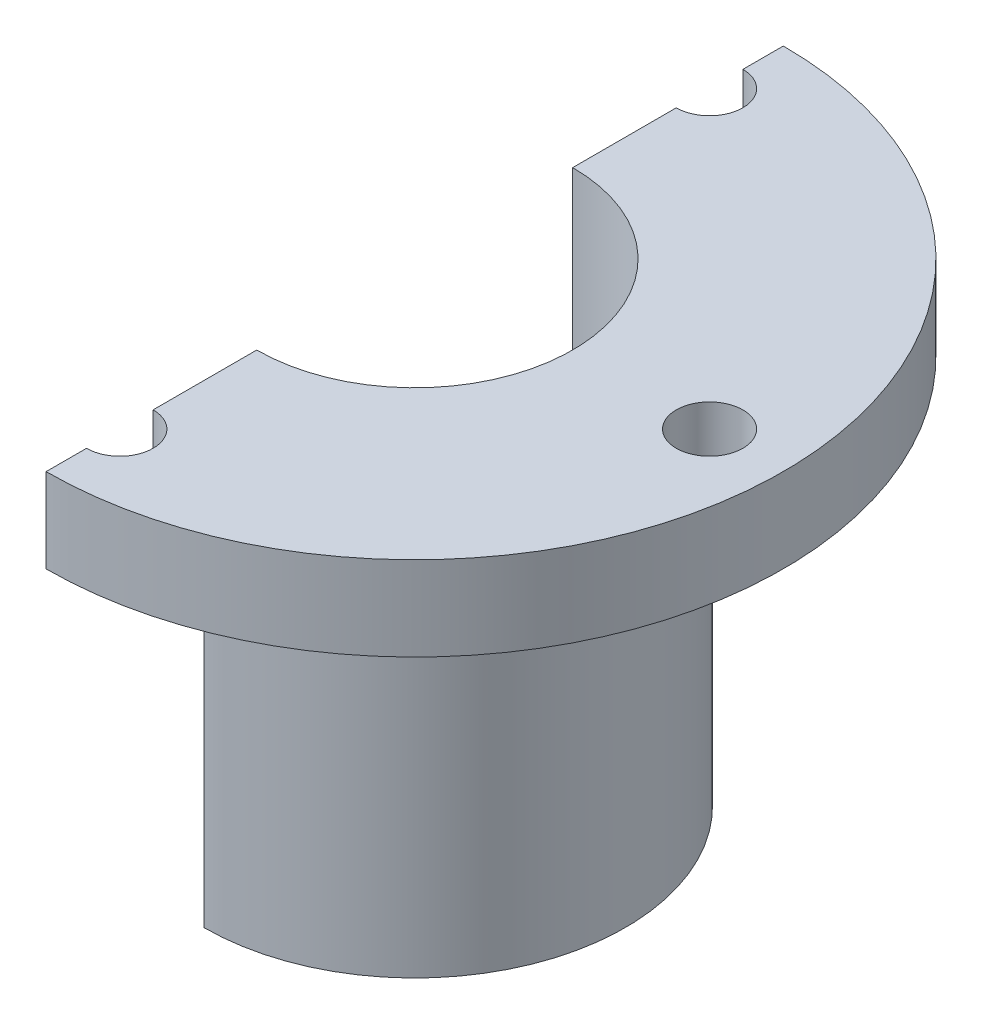
SolidWorks part; units mm, degrees
ref_plane "Plan1" through (0, 0, 0) normal (0, 0, 1) x (1, 0, 0)
ref_plane "Plan2" through (0, 0, 0) normal (0, 1, 0) x (1, 0, 0)
ref_plane "Plan3" through (0, 0, 0) normal (1, 0, 0) x (0, 0, -1)
sketch "Esquisse1" plane through (0, 0, 0) normal (1, 0, 0) x (0, 0, -1)
  line L0 (0, 0) -> (0, 40) construction
  line L1 (-7, 0) -> (-7, 6)
  line L2 (-7, 6) -> (-15, 6)
  line L3 (-7, 0) -> (-17.5, 0)
  line L4 (-17.5, 0) -> (-17.5, -20)
  line L5 (-17.5, -20) -> (-20, -20)
  line L6 (-20, -20) -> (-20, 17)
  line L7 (-20, 17) -> (-35, 17)
  line L8 (-35, 17) -> (-35, 25)
  line L9 (-35, 25) -> (-15, 25)
  line L10 (-15, 25) -> (-15, 6)
  dimension "D1" = 17.5
  dimension "D2" = 20
  dimension "D3" = 7
  dimension "D4" = 35
  dimension "D5" = 8
  dimension "D6" = 6
revolve "Base-Révolution" add sketch "Esquisse1" angle 180 about L0
sketch "Esquisse2" plane through (0, 25, 0) normal (0, 1, 0) x (-1, 0, 0)
  circle A0 centre (0, -28) radius 3.1623 construction
  circle A1 centre (0, -28) radius 3.1623
  circle A2 centre (0, 28) radius 3.1623 construction
  circle A3 centre (0, 28) radius 3.1623
  circle A4 centre (-28, 0) radius 3.1623 construction
  circle A5 centre (-28, 0) radius 3.1623
extrude "Enlèv. mat.-Extru.1" cut sketch "Esquisse2" against normal through all
